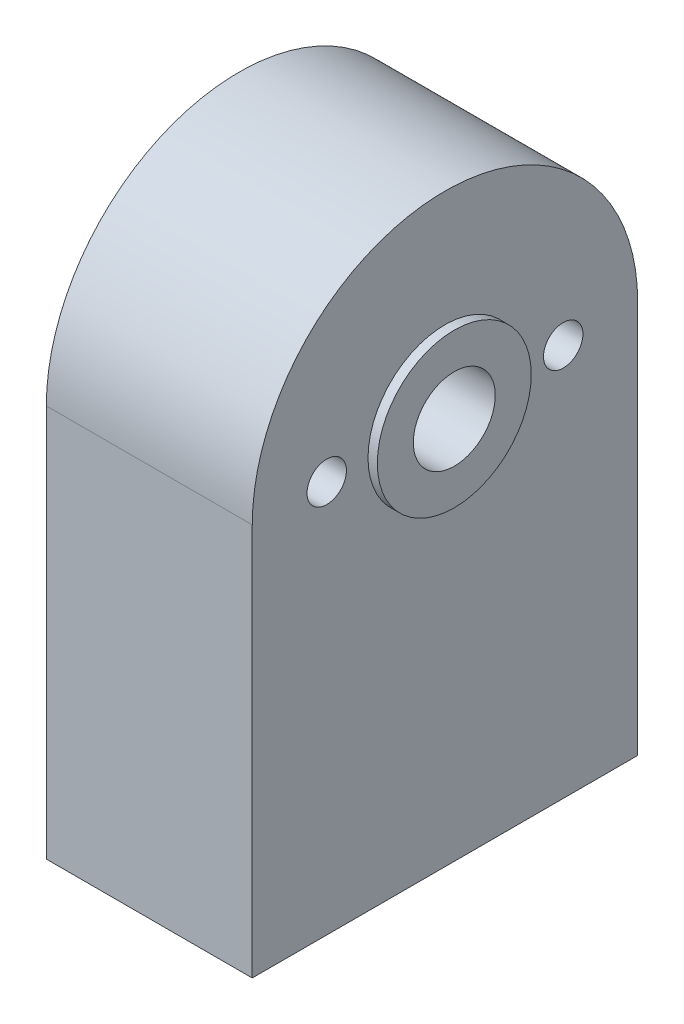
SolidWorks part; units mm, degrees
ref_plane "Front Plane" through (0, 0, 0) normal (0, 0, 1) x (1, 0, 0)
ref_plane "Top Plane" through (0, 0, 0) normal (0, 1, 0) x (1, 0, 0)
ref_plane "Right Plane" through (0, 0, 0) normal (1, 0, 0) x (0, 0, -1)
sketch "Sketch1" plane through (0, 0, 0) normal (1, 0, 0) x (0, 0, -1)
  line L0 (-15.525, -31.615) -> (15.525, -31.615)
  line L1 (15.525, -31.615) -> (15.525, 0)
  line L2 (-15.525, -31.615) -> (-15.525, 0)
  line L3 (-15.525, 0) -> (15.525, 0) construction
  line L4 (0, 15.525) -> (0, -31.615) construction
  arc A0 (-15.525, 0) -> (15.525, 0) centre (0, 0) cw
  dimension "D2" = 47.14
  dimension "D1" = 31.05
extrude "Boss-Extrude1" add sketch "Sketch1" along normal blind 16.59
sketch "Sketch2" plane through (16.59, 0, 0) normal (1, 0, 0) x (0, 0, -1)
  circle A0 centre (0, 0) radius 6.2
  dimension "D1" = 12.4
extrude "Boss-Extrude2" add sketch "Sketch2" along normal blind 0.75
sketch "Sketch3" plane through (17.34, 0, 0) normal (1, 0, 0) x (0, 0, -1)
  line L0 (-9.525, 0) -> (9.525, 0) construction
  circle A0 centre (0, 0) radius 3.3
  circle A1 centre (-9.525, 0) radius 1.5875
  circle A2 centre (9.525, 0) radius 1.5875
  point P7 (0, 0)
  dimension "D1" = 6.6
  dimension "D3" = 3.175
  dimension "0.125in" = 3.175
  dimension "D2" = 19.05
extrude "Cut-Extrude1" cut sketch "Sketch3" against normal through all
